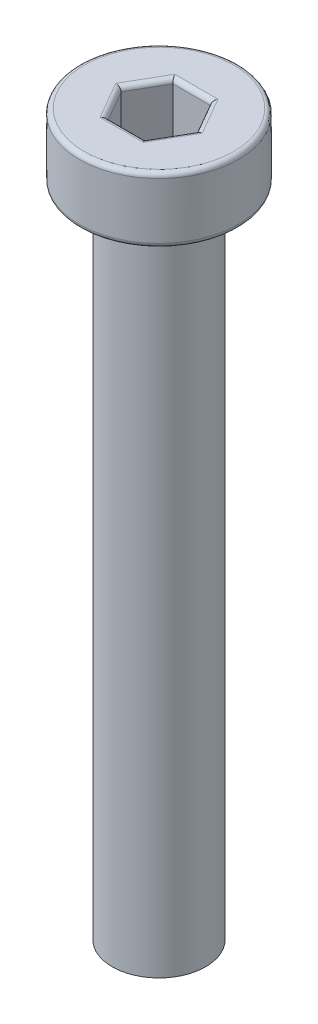
SolidWorks part; units mm, degrees
ref_plane "Front Plane" through (0, 0, 0) normal (0, 0, 1) x (1, 0, 0)
ref_plane "Top Plane" through (0, 0, 0) normal (0, 1, 0) x (1, 0, 0)
ref_plane "Right Plane" through (0, 0, 0) normal (1, 0, 0) x (0, 0, -1)
sketch "Sketch1" plane through (0, 0, 0) normal (0, 0, 1) x (1, 0, 0)
  line L0 (0, 21.3223) -> (0, -43.638) construction
sketch "Sketch2" plane through (0, 0, 0) normal (0, 0, 1) x (1, 0, 0)
  line L0 (0, 3.5) -> (4.25, 3.5)
  line L1 (0, 200021.3223) -> (0, -200043.638) construction
  line L2 (4.25, 3.5) -> (4.25, 0)
  line L3 (4.25, 0) -> (2.5, 0)
  line L4 (2.5, 0) -> (2.5, -35)
  line L5 (2.5, -35) -> (0, -35)
  line L6 (0, -35) -> (0, 3.5)
  dimension "D1" = 2.5
  dimension "D2" = 4.25
  dimension "D3" = 3.5
  dimension "D4" = 35
revolve "Revolve1" add sketch "Sketch2" angle 360 about L0
sketch "Sketch3" plane through (0, 3.5, 0) normal (0, 1, 0) x (1, 0, 0)
  line L0 (0, 0) -> (2.0207, 0) construction
  line L1 (2.0207, 0) -> (1.0104, 1.75)
  line L2 (1.0104, 1.75) -> (-1.0104, 1.75)
  line L3 (-1.0104, 1.75) -> (-2.0207, 0)
  line L4 (-2.0207, 0) -> (-1.0104, -1.75)
  line L5 (-1.0104, -1.75) -> (1.0104, -1.75)
  line L6 (1.0104, -1.75) -> (2.0207, 0)
  circle A0 centre (0, 0) radius 1.75 construction
  dimension "D1" = 3.5
extrude "Cut-Extrude1" cut sketch "Sketch3" against normal blind 3
fillet "Fillet1" radius 0.25 9 edges at (-2.5, 0, 0) (-4.25, 0, 0) (-4.25, 3.5, 0) (0, 3.5, -1.75) (-1.5155, 3.5, -0.875) (-1.5155, 3.5, 0.875) (0, 3.5, 1.75) (1.5155, 3.5, 0.875) (1.5155, 3.5, -0.875)
